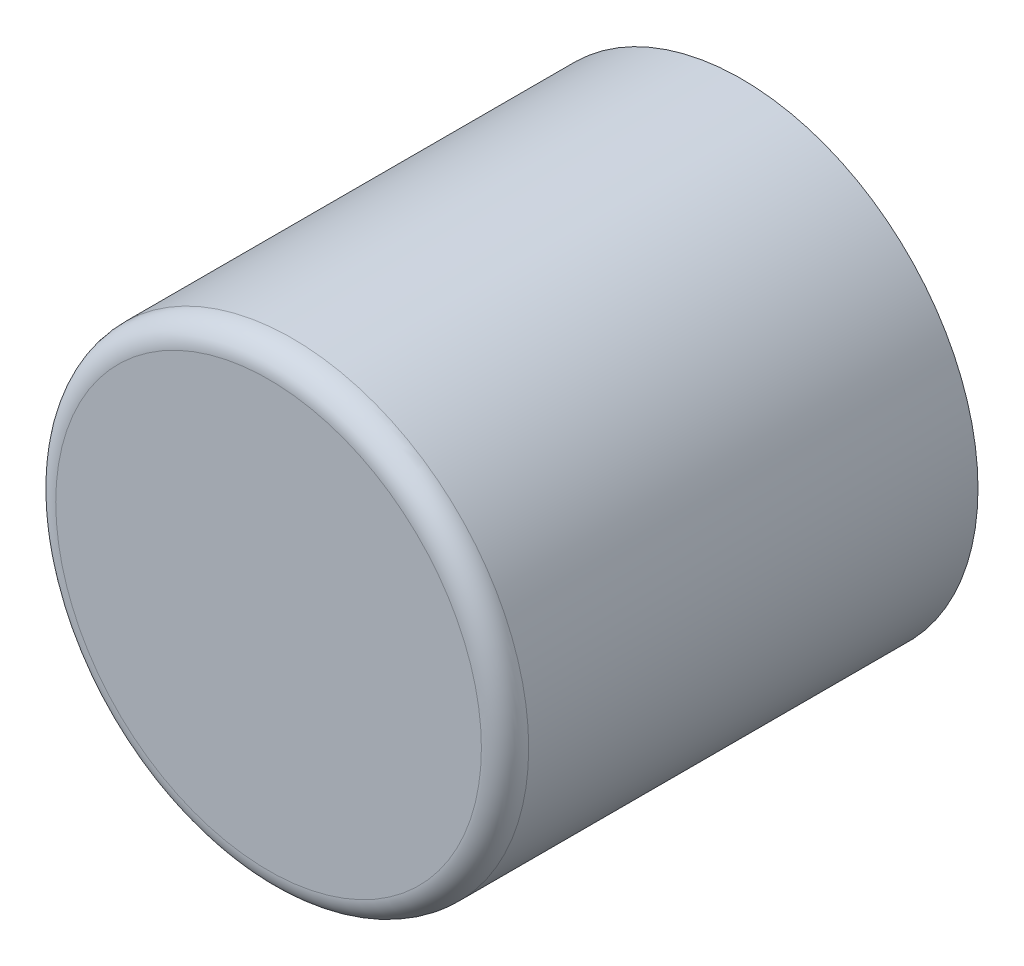
SolidWorks part; units mm, degrees
ref_plane "前视基准面" through (0, 0, 0) normal (0, 0, 1) x (1, 0, 0)
ref_plane "上视基准面" through (0, 0, 0) normal (0, 1, 0) x (1, 0, 0)
ref_plane "右视基准面" through (0, 0, 0) normal (1, 0, 0) x (0, 0, -1)
other "Configuration Table"
sketch "草图1" plane through (0, 0, 0) normal (0, 0, 1) x (1, 0, 0)
  circle A0 centre (0.6678, 2.7026) radius 1
  dimension "D1" = 2
extrude "凸台-拉伸1" add sketch "草图1" along normal mid plane 2
fillet "圆角1" radius 0.1 1 edges at (1.6678, 2.7026, 1)
